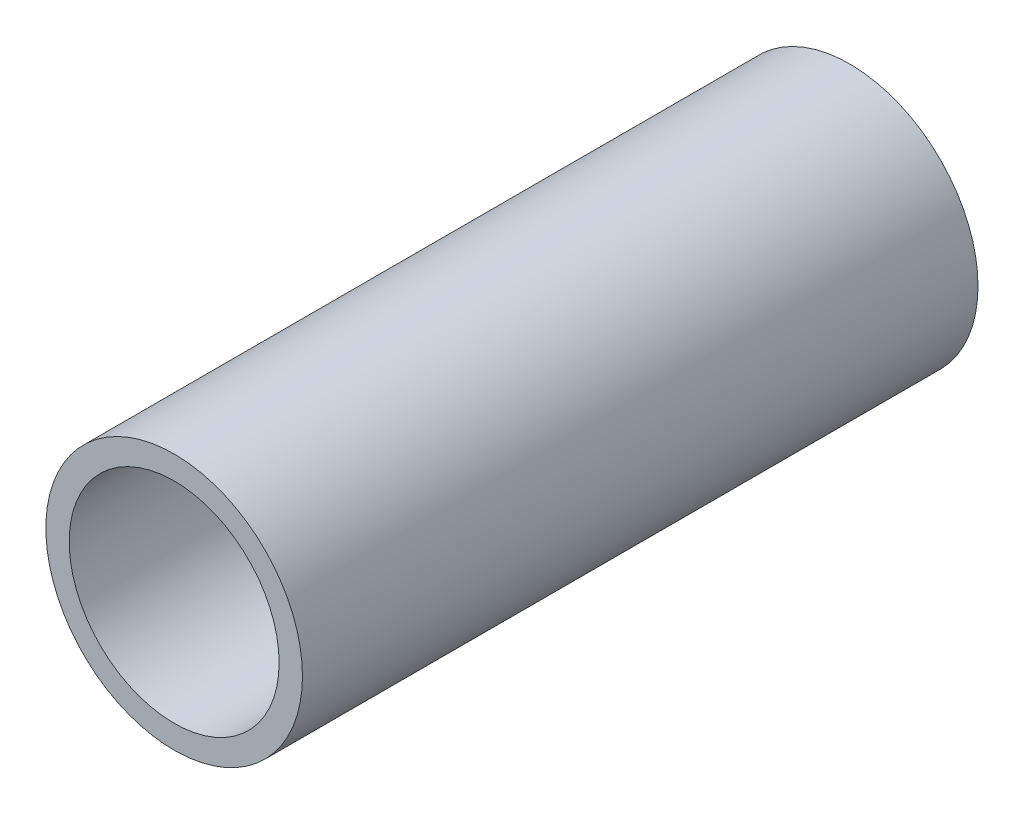
SolidWorks part; units mm, degrees
material "Plain Carbon Steel"
ref_plane "Front Plane" through (0, 0, 0) normal (0, 0, 1) x (1, 0, 0)
ref_plane "Top Plane" through (0, 0, 0) normal (0, 1, 0) x (1, 0, 0)
ref_plane "Right Plane" through (0, 0, 0) normal (1, 0, 0) x (0, 0, -1)
sketch "Sketch2" plane through (0, 0, 0) normal (0, 0, 1) x (1, 0, 0)
  circle A0 centre (0, 0) radius 8.7312
  circle A1 centre (0, 0) radius 7.1438
  dimension "D1" = 17.4625
  dimension "D2" = 14.2875
extrude "Boss-Extrude1" add sketch "Sketch2" against normal blind 45.974
